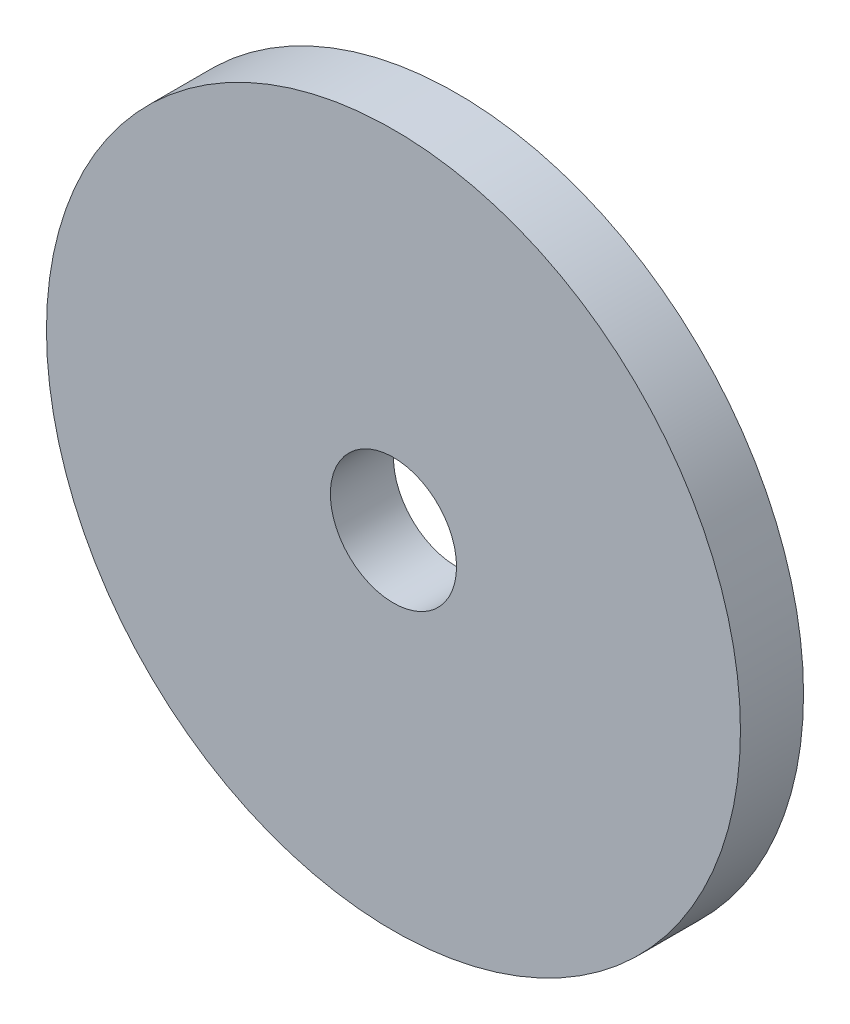
SolidWorks part; units mm, degrees
ref_plane "前视基准面" through (0, 0, 0) normal (0, 0, 1) x (1, 0, 0)
ref_plane "上视基准面" through (0, 0, 0) normal (0, 1, 0) x (1, 0, 0)
ref_plane "右视基准面" through (0, 0, 0) normal (1, 0, 0) x (0, 0, -1)
sketch "草图1" plane through (0, 0, 0) normal (0, 0, 1) x (1, 0, 0)
  circle A0 centre (0, 0) radius 11
  circle A1 centre (0, 0) radius 2
  dimension "D1" = 22
  dimension "D2" = 4
extrude "凸台-拉伸1" add sketch "草图1" along normal blind 2
